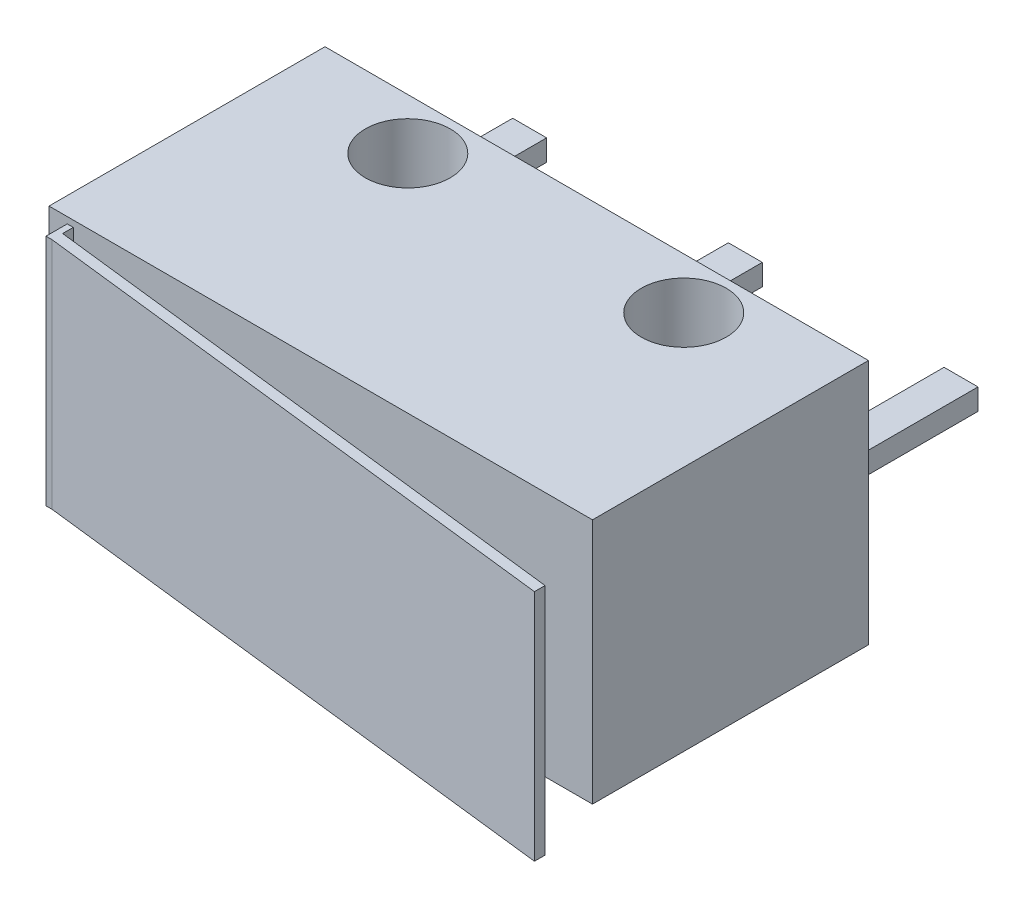
SolidWorks part; units mm, degrees
ref_plane "前视基准面" through (0, 0, 0) normal (0, 0, 1) x (1, 0, 0)
ref_plane "上视基准面" through (0, 0, 0) normal (0, 1, 0) x (1, 0, 0)
ref_plane "右视基准面" through (0, 0, 0) normal (1, 0, 0) x (0, 0, -1)
sketch "草图1" plane through (0, 0, 0) normal (0, 1, 0) x (1, 0, 0)
  line L0 (0, -12.5051) -> (0, 12.5051) construction
  line L1 (-6.4, -3.25) -> (6.4, -3.25)
  line L2 (-6.4, -3.25) -> (-6.4, 3.25)
  line L3 (-6.4, 3.25) -> (6.4, 3.25)
  line L4 (6.4, -3.25) -> (6.4, 3.25)
  line L5 (-6.4, -3.25) -> (6.4, 3.25) construction
  line L6 (-6.4, 3.25) -> (6.4, -3.25) construction
  line L7 (9.9042, 2.05) -> (-9.9042, 2.05) construction
  circle A0 centre (-3.25, 2.05) radius 1
  circle A1 centre (3.25, 2.05) radius 1
  point P0 (0, 0)
  point P9 (0, 0)
  point P12 (0, 2.05)
  point P14 (0, 0)
  point P15 (0, 0)
  dimension "D4" = 2
  dimension "D1" = 12.8
  dimension "D2" = 6.5
  dimension "D3" = 5.3
  dimension "D5" = 3.25
extrude "凸台-拉伸1" add sketch "草图1" along normal blind 5.8
sketch "草图2" plane through (0, 0, -3.25) normal (0, 0, -1) x (-1, 0, 0)
  line L0 (0, 0) -> (0, 5.8) construction
  line L1 (-6.4, 5.8) -> (6.4, 5.8) construction
  line L2 (-6.9667, 2.8013) -> (6.9667, 2.8013) construction
  line L3 (-0.4, 2.5513) -> (-0.4, 3.0513)
  line L4 (4.68, 2.5513) -> (5.48, 2.5513)
  line L5 (4.68, 2.5513) -> (4.68, 3.0513)
  line L6 (4.68, 3.0513) -> (5.48, 3.0513)
  line L7 (5.48, 2.5513) -> (5.48, 3.0513)
  line L8 (4.68, 2.5513) -> (5.48, 3.0513) construction
  line L9 (4.68, 3.0513) -> (5.48, 2.5513) construction
  line L10 (-0.4, 2.5513) -> (0.4, 2.5513)
  line L11 (0.4, 2.5513) -> (0.4, 3.0513)
  line L12 (-0.4, 3.0513) -> (0.4, 3.0513)
  line L13 (-5.48, 2.5513) -> (-5.48, 3.0513)
  line L14 (-5.48, 2.5513) -> (-4.68, 2.5513)
  line L15 (-4.68, 2.5513) -> (-4.68, 3.0513)
  line L16 (-5.48, 3.0513) -> (-4.68, 3.0513)
  point P5 (5.08, 2.8013)
  point P8 (0, 2.8013)
  point P15 (0, 2.8013)
  point P20 (-5.08, 2.8013)
  dimension "D1" = 0.5
  dimension "D2" = 0.8
  dimension "D4" = 5.08
  dimension "D3" = 3
extrude "凸台-拉伸2" add sketch "草图2" along normal blind 3.5
sketch "草图4" plane through (0, 0, 3.25) normal (0, 0, 1) x (1, 0, 0)
  line L0 (0, 0) -> (-5.9, 0) construction
  line L1 (-6.4, 0) -> (6.4, 0) construction
  line L2 (-5.9, 0) -> (-5.9, 5.8) construction
  line L3 (-6.4, 5.8) -> (6.4, 5.8) construction
  line L5 (-5.971, 0.15) -> (-5.829, 0.15)
  line L6 (-5.971, 0.15) -> (-5.971, 5.65)
  line L7 (-5.971, 5.65) -> (-5.829, 5.65)
  line L8 (-5.829, 0.15) -> (-5.829, 5.65)
  line L9 (-5.971, 0.15) -> (-5.829, 5.65) construction
  line L10 (-5.971, 5.65) -> (-5.829, 0.15) construction
  point P5 (-5.9, 2.9)
  dimension "D1" = 0.5
  dimension "D2" = 5.5
extrude "凸台-拉伸4" add sketch "草图4" along normal blind 0.5
sketch "草图6" plane through (0, 0.15, 0) normal (0, -1, 0) x (1, 0, 0)
  line L0 (-5.829, 3.75) -> (-5.829, 3.5)
  line L1 (-5.829, 3.75) -> (7.0312, 5.2487)
  line L2 (-5.829, 3.5) -> (7.0312, 4.9987)
  line L3 (7.0312, 5.2487) -> (7.0312, 4.9987)
  line L4 (-5.829, 3.75) -> (-5.829, 3.25) construction
extrude "凸台-拉伸5" add sketch "草图6" against normal blind 5.5
